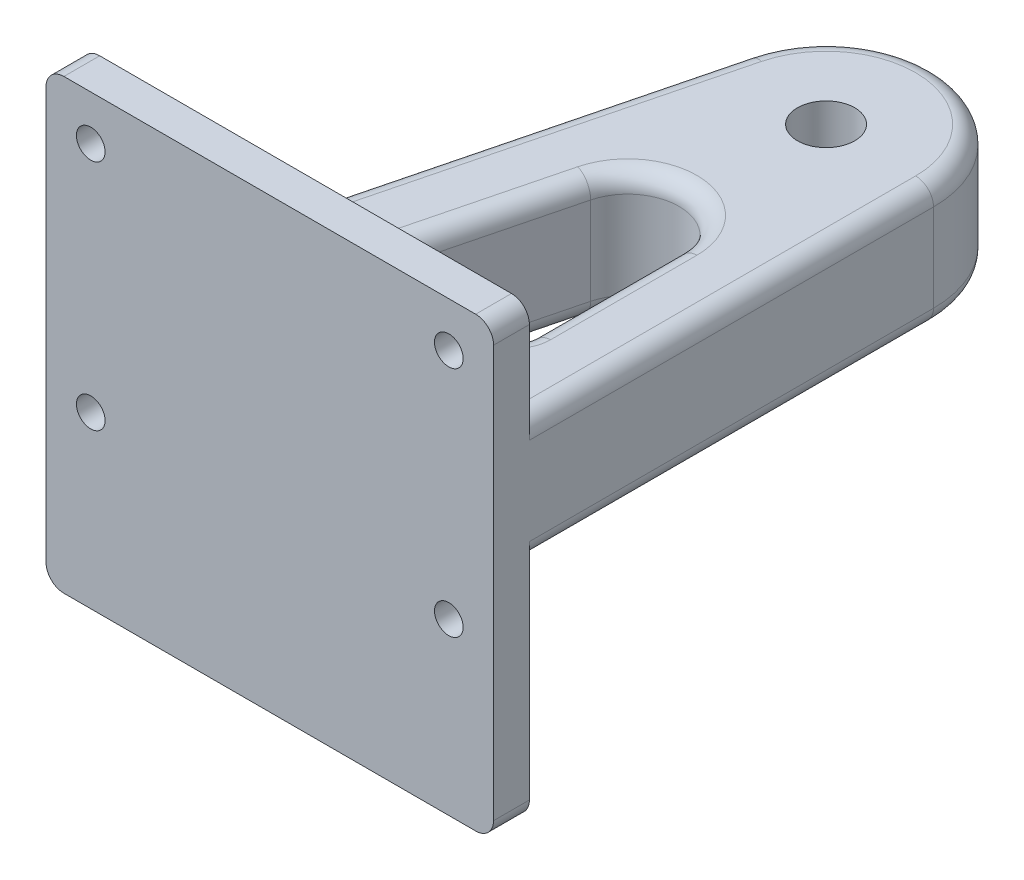
SolidWorks part; units mm, degrees
material "ABS"
ref_plane "Front Plane" through (0, 0, 0) normal (0, 0, 1) x (1, 0, 0)
ref_plane "Top Plane" through (0, 0, 0) normal (0, 1, 0) x (1, 0, 0)
ref_plane "Right Plane" through (0, 0, 0) normal (1, 0, 0) x (0, 0, -1)
sketch "Sketch1" plane through (0, 0, 0) normal (0, 0, 1) x (1, 0, 0)
  line L1 (-12.5, 12.5) -> (12.5, 12.5)
  line L2 (-12.5, 12.5) -> (-12.5, -12.5)
  line L3 (-12.5, -12.5) -> (12.5, -12.5)
  line L4 (12.5, 12.5) -> (12.5, -12.5)
  line L5 (-12.5, 12.5) -> (12.5, -12.5) construction
  line L6 (-12.5, -12.5) -> (12.5, 12.5) construction
  point P0 (0, 0)
  dimension "D1" = 25
  dimension "D2" = 25
extrude "Boss-Extrude1" add sketch "Sketch1" along normal blind 2
sketch "Sketch2" plane through (0, 0, 2) normal (0, 0, 1) x (1, 0, 0)
  line L0 (-12.5, 12.5) -> (-12.5, -12.5) construction
  line L1 (12.5, 12.5) -> (-12.5, 12.5) construction
  circle A0 centre (-10, 10) radius 0.8
  dimension "D1" = 1.6
  dimension "D2" = 2.5
  dimension "D3" = 2.5
extrude "Cut-Extrude1" cut sketch "Sketch2" against normal through all
pattern_linear "LPattern1" count 2 spacing 20 along (1, 0, 0) count 2 spacing 13 along (0, -1, 0) of "Cut-Extrude1"
sketch "Sketch3" plane through (0, 0, 0) normal (0, 1, 0) x (1, 0, 0)
  line L0 (12.5, 0) -> (-5.424, 0)
  line L1 (-5.424, 0) -> (0.6847, 24.0494)
  line L2 (12.5, 22.5722) -> (12.5, 0)
  line L3 (1.3611, 3.4468) -> (7.228, 3.4468)
  line L4 (8.228, 4.4468) -> (8.228, 12.6287)
  line L5 (0.3918, 4.6929) -> (2.5867, 13.334)
  arc A0 (0.6847, 24.0494) -> (12.5, 22.5722) centre (6.5, 22.5722) cw
  arc A1 (2.5867, 13.334) -> (8.228, 12.6287) centre (5.3633, 12.6287) cw
  arc A2 (7.228, 3.4468) -> (8.228, 4.4468) centre (7.228, 4.4468) ccw
  arc A3 (1.3611, 3.4468) -> (0.3918, 4.6929) centre (1.3611, 4.4468) cw
  circle A4 centre (6.5, 22.5722) radius 1.6
  point P13 (6.5, 17.8826)
  point P17 (12.5, 22.5722)
  point P19 (2.5867, 13.334)
  dimension "D1" = 6
  dimension "D2" = 1
  dimension "D3" = 3.2
extrude "Boss-Extrude2" add sketch "Sketch3" along normal blind 6.9
fillet "Fillet1" radius 1 22 edges at (12.5, 0, -11.2861) (7.2443, 0, -28.5259) (12.5, 6.9, -11.2861) (7.2443, 6.9, -28.5259) (7.9351, 0, -3.7396) (4.2945, 0, -3.4468) (0.5717, 0, -3.8328) (1.4893, 0, -9.0135) (5.7186, 0, -15.4713) (7.9351, 6.9, -3.7396) (4.2945, 6.9, -3.4468) (0.5717, 6.9, -3.8328) (1.4893, 6.9, -9.0135) (5.7186, 6.9, -15.4713) (-12.5, -12.5, 1) (12.5, -12.5, 1) (12.5, 12.5, 1) (-12.5, 12.5, 1) (-2.3697, 0, -12.0247) (-2.3697, 6.9, -12.0247) (8.228, 0, -8.5377) (8.228, 6.9, -8.5377)
